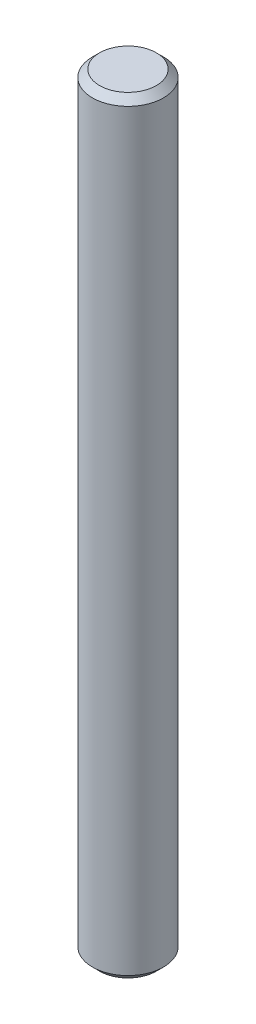
SolidWorks part; units mm, degrees
ref_plane "前视基准面" through (0, 0, 0) normal (0, 0, 1) x (1, 0, 0)
ref_plane "上视基准面" through (0, 0, 0) normal (0, 1, 0) x (1, 0, 0)
ref_plane "右视基准面" through (0, 0, 0) normal (1, 0, 0) x (0, 0, -1)
other "Configuration Table"
sketch "草图1" plane through (0, 0, 0) normal (0, 0, 1) x (1, 0, 0)
  line L0 (0, 17.9143) -> (0, -10.0949) construction
  line L1 (0, 54) -> (5, 54)
  line L2 (5, 54) -> (5, 30)
  line L4 (5, 30) -> (5, -30)
  line L6 (5, -30) -> (5, -54)
  line L7 (5, -54) -> (0, -54)
  line L8 (0, 0) -> (25.4592, 0) construction
  line L9 (0, 54) -> (0, -54)
  point P13 (7.4508, -30)
  point P14 (0, 0)
  dimension "D1" = 5
  dimension "D3" = 60
  dimension "D4" = 24
  dimension "D5" = 24
revolve "旋转1" add sketch "草图1" angle 360 about L9
chamfer "倒角1" distance 1 angle 45 2 edges at (-5, -54, 0) (-5, 54, 0)
